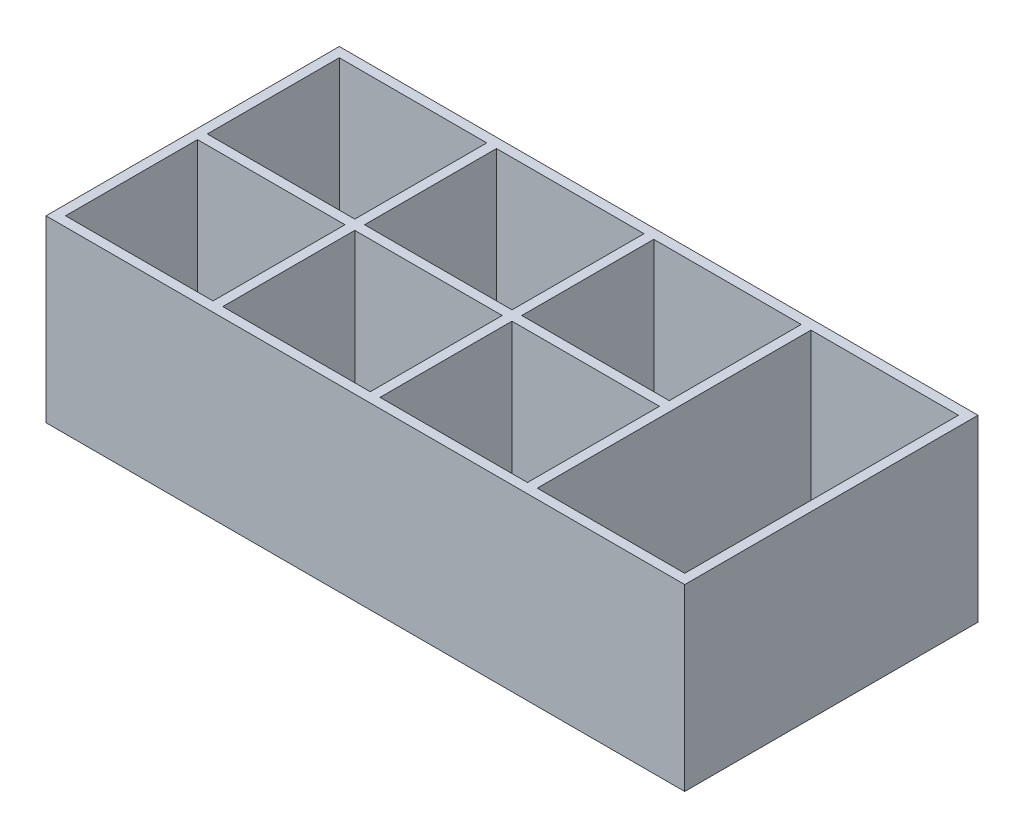
SolidWorks part; units mm, degrees
ref_plane "Front Plane" through (0, 0, 0) normal (0, 0, 1) x (1, 0, 0)
ref_plane "Top Plane" through (0, 0, 0) normal (0, 1, 0) x (1, 0, 0)
ref_plane "Right Plane" through (0, 0, 0) normal (1, 0, 0) x (0, 0, -1)
sketch "Sketch1" plane through (0, 0, 0) normal (0, 1, 0) x (1, 0, 0)
  line L1 (-98, -45) -> (98, -45)
  line L2 (-98, -45) -> (-98, 45)
  line L3 (-98, 45) -> (98, 45)
  line L4 (98, -45) -> (98, 45)
  line L5 (-98, -45) -> (98, 45) construction
  line L6 (-98, 45) -> (98, -45) construction
  point P0 (0, 0)
  dimension "D1" = 196
  dimension "D2" = 90
extrude "Boss-Extrude1" add sketch "Sketch1" along normal blind 55
sketch "Sketch2" plane through (0, 55, 0) normal (0, 1, 0) x (1, 0, 0)
  line L0 (98, -45) -> (98, 45) construction
  line L1 (-95, 42) -> (-49.75, 42)
  line L2 (-95, 42) -> (-95, 1.5)
  line L3 (-95, 1.5) -> (-49.75, 1.5)
  line L4 (-49.75, 42) -> (-49.75, 1.5)
  line L5 (-95, 42) -> (-49.75, 1.5) construction
  line L6 (-95, 1.5) -> (-49.75, 42) construction
  line L7 (-95, -1.5) -> (-49.75, -1.5)
  line L8 (-95, -1.5) -> (-95, -42)
  line L9 (-95, -42) -> (-49.75, -42)
  line L10 (-49.75, -1.5) -> (-49.75, -42)
  line L11 (-95, -1.5) -> (-49.75, -42) construction
  line L12 (-95, -42) -> (-49.75, -1.5) construction
  line L13 (-46.75, 42) -> (-1.5, 42)
  line L14 (-46.75, 42) -> (-46.75, 1.5)
  line L15 (-46.75, 1.5) -> (-1.5, 1.5)
  line L16 (-1.5, 42) -> (-1.5, 1.5)
  line L17 (-46.75, 42) -> (-1.5, 1.5) construction
  line L18 (-46.75, 1.5) -> (-1.5, 42) construction
  line L19 (-46.75, -1.5) -> (-1.5, -1.5)
  line L20 (-46.75, -1.5) -> (-46.75, -42)
  line L21 (-46.75, -42) -> (-1.5, -42)
  line L22 (-1.5, -1.5) -> (-1.5, -42)
  line L23 (-46.75, -1.5) -> (-1.5, -42) construction
  line L24 (-46.75, -42) -> (-1.5, -1.5) construction
  line L25 (1.5, 42) -> (46.75, 42)
  line L26 (1.5, 42) -> (1.5, 1.5)
  line L27 (1.5, 1.5) -> (46.75, 1.5)
  line L28 (46.75, 42) -> (46.75, 1.5)
  line L29 (1.5, 42) -> (46.75, 1.5) construction
  line L30 (1.5, 1.5) -> (46.75, 42) construction
  line L31 (46.75, -1.5) -> (1.5, -1.5)
  line L32 (46.75, -1.5) -> (46.75, -42)
  line L33 (46.75, -42) -> (1.5, -42)
  line L34 (1.5, -1.5) -> (1.5, -42)
  line L35 (46.75, -1.5) -> (1.5, -42) construction
  line L36 (46.75, -42) -> (1.5, -1.5) construction
  line L37 (49.75, -42) -> (95, -42)
  line L38 (49.75, -42) -> (49.75, 42)
  line L39 (49.75, 42) -> (95, 42)
  line L40 (95, -42) -> (95, 42)
  line L41 (49.75, -42) -> (95, 42) construction
  line L42 (49.75, 42) -> (95, -42) construction
  line L43 (98, 45) -> (-98, 45) construction
  line L44 (-98, -45) -> (98, -45) construction
  point P0 (-72.375, 21.75)
  point P5 (-72.375, -21.75)
  point P10 (-24.125, 21.75)
  point P15 (-24.125, -21.75)
  point P20 (24.125, 21.75)
  point P25 (24.125, -21.75)
  point P30 (72.375, 0)
  dimension "D1" = 3
  dimension "D2" = 3
  dimension "D3" = 3
  dimension "D4" = 45.25
  dimension "D5" = 45.25
  dimension "D6" = 3
  dimension "D7" = 45.25
  dimension "D8" = 3
  dimension "D9" = 3
  dimension "D10" = 45.25
  dimension "D11" = 3
  dimension "D12" = 3
  dimension "D13" = 3
  dimension "D14" = 40.5
  dimension "D15" = 40.5
  dimension "D16" = 40.5
  dimension "D17" = 3
  dimension "D18" = 3
  dimension "D19" = 3
  dimension "D20" = 3
  dimension "D21" = 3
  dimension "D22" = 3
  dimension "D23" = 40.5
  dimension "D24" = 40.5
  dimension "D25" = 40.5
  dimension "D26" = 45.25
  dimension "D27" = 45.25
  dimension "D28" = 45.25
extrude "Cut-Extrude1" cut sketch "Sketch2" against normal blind 52
